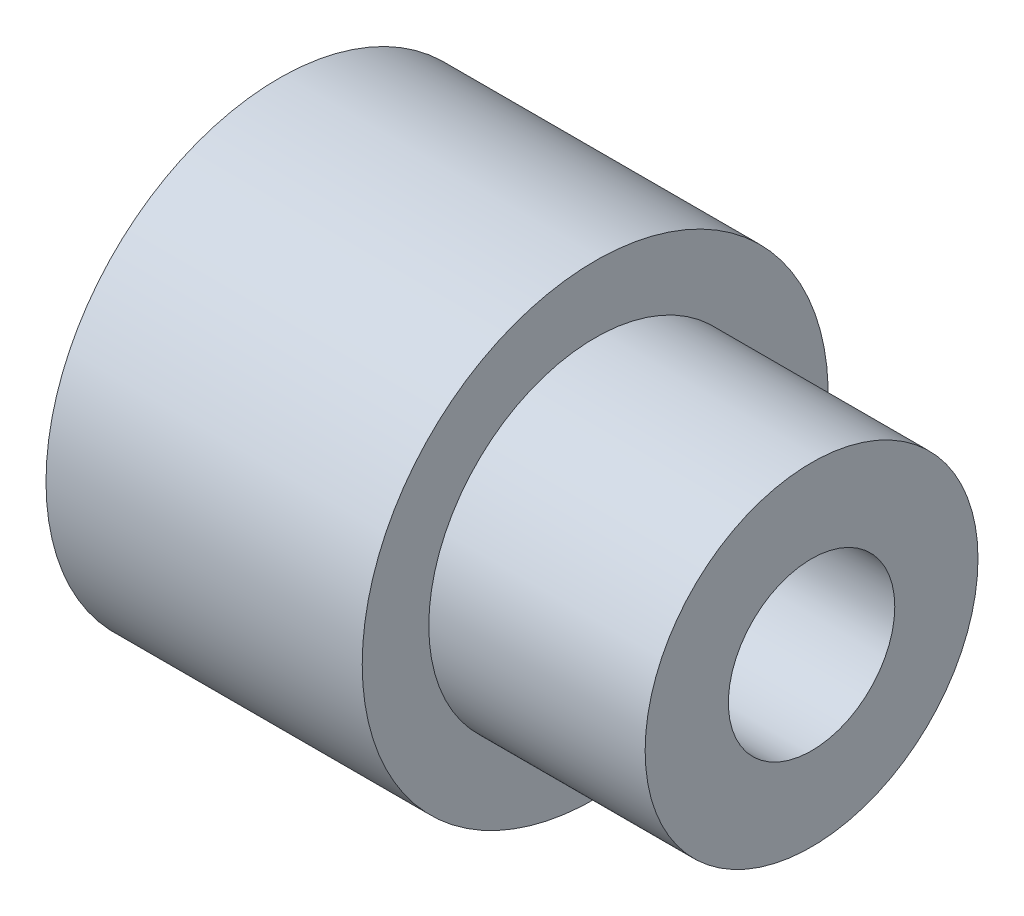
SolidWorks part; units mm, degrees
ref_plane "Front Plane" through (0, 0, 0) normal (0, 0, 1) x (1, 0, 0)
ref_plane "Top Plane" through (0, 0, 0) normal (0, 1, 0) x (1, 0, 0)
ref_plane "Right Plane" through (0, 0, 0) normal (1, 0, 0) x (0, 0, -1)
sketch "Sketch1" plane through (0, 0, 0) normal (1, 0, 0) x (0, 0, -1)
  circle A0 centre (0, 0) radius 10
  dimension "D1" = 20
extrude "Boss-Extrude1" add sketch "Sketch1" against normal blind 13
sketch "Sketch2" plane through (-13, 0, 0) normal (-1, 0, 0) x (0, 0, 1)
  circle A0 centre (0, 0) radius 14
  dimension "D1" = 28
extrude "Boss-Extrude2" add sketch "Sketch2" along normal blind 19
sketch "Sketch3" plane through (-32, 0, 0) normal (-1, 0, 0) x (0, 0, 1)
  circle A0 centre (0, 0) radius 11
  dimension "D1" = 22
extrude "Cut-Extrude1" cut sketch "Sketch3" against normal blind 6
sketch "Sketch4" plane through (-26, 0, 0) normal (-1, 0, 0) x (0, 0, 1)
  circle A0 centre (0, 0) radius 9
  dimension "D1" = 18
extrude "Cut-Extrude2" cut sketch "Sketch4" against normal blind 10
sketch "Sketch5" plane through (0, 0, 0) normal (1, 0, 0) x (0, 0, -1)
  circle A0 centre (0, 0) radius 5
  dimension "D1" = 10
extrude "Cut-Extrude3" cut sketch "Sketch5" against normal through all
fillet "Fillet1" radius 0.05 1 edges at (-32, 0, 11)
